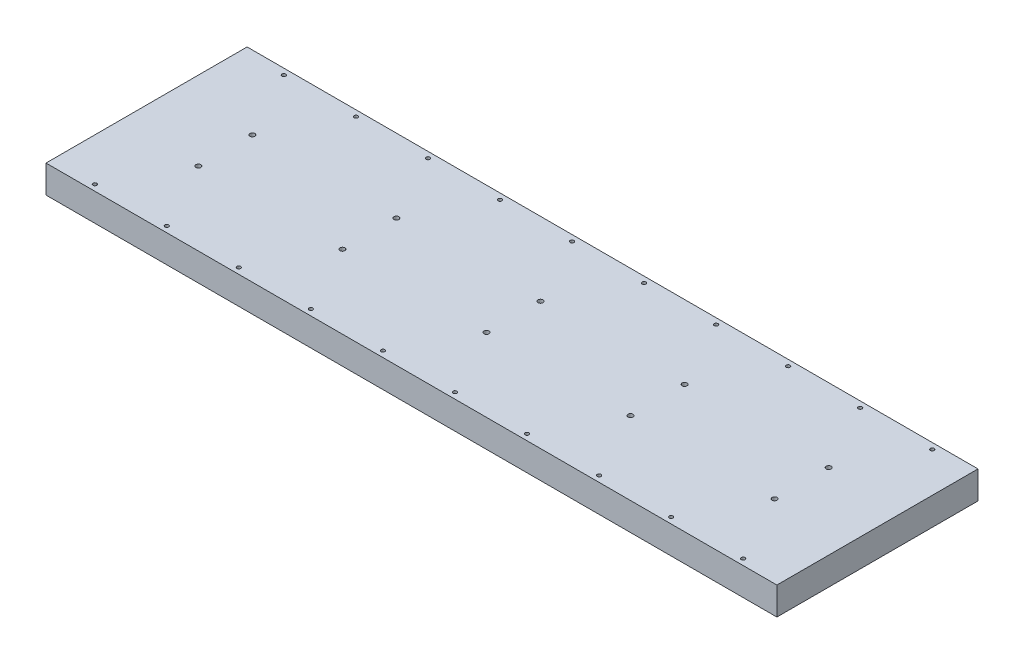
SolidWorks part; units mm, degrees
ref_plane "Front Plane" through (0, 0, 0) normal (0, 0, 1) x (1, 0, 0)
ref_plane "Top Plane" through (0, 0, 0) normal (0, 1, 0) x (1, 0, 0)
ref_plane "Right Plane" through (0, 0, 0) normal (1, 0, 0) x (0, 0, -1)
sketch "Sketch1" plane through (0, 0, 0) normal (0, 1, 0) x (1, 0, 0)
  line L1 (-243.5, 67) -> (243.5, 67)
  line L2 (-243.5, 67) -> (-243.5, -67)
  line L3 (-243.5, -67) -> (243.5, -67)
  line L4 (243.5, 67) -> (243.5, -67)
  line L5 (-243.5, 67) -> (243.5, -67) construction
  line L6 (-243.5, -67) -> (243.5, 67) construction
  point P0 (0, 0)
  dimension "D1" = 134
  dimension "D2" = 487
extrude "Boss-Extrude1" add sketch "Sketch1" along normal blind 18.5
hole_wizard "Tap Drill for M4x0.7 Tap1" positions "Sketch2" profile "Sketch3" hole size "M4x0.7" standard "ANSI Metric"
sketch "Sketch2" plane through (0, 18.5, 0) normal (0, 1, 0) x (1, 0, 0)
  line L0 (-191, -18) -> (-191, 18) construction
  line L3 (-243.5, 67) -> (-243.5, -67) construction
  point P0 (-191, 18)
  point P2 (-191, -18)
  point P10 (-191, 0)
  dimension "D1" = 36
  dimension "D2" = 52.5
sketch "Sketch3" plane through (-191, 18.5, -18) normal (1, 0, 0) x (0, 0, 1)
  line L0 (0, 0) -> (0, 18.3714)
  line L1 (0, 18.3714) -> (1.65, 17.38)
  line L2 (1.65, 17.38) -> (1.65, 0)
  line L5 (1.65, 0) -> (0, 0)
  line L10 (0, 18.3714) -> (-1.65, 17.38) construction
  line L11 (0, -6.35) -> (0, 107.95) construction
  dimension "Hole Dia." = 3.3
  dimension "Hole Depth" = 17.38
  dimension "Drill Angle" = 118
hole_wizard "Tap Drill for M3x0.5 Tap1" positions "Sketch4" profile "Sketch5" hole size "M3x0.5" standard "ANSI Metric"
sketch "Sketch4" plane through (0, 18.5, 0) normal (0, 1, 0) x (1, 0, 0)
  line L0 (-167, -63) -> (-167, 63) construction
  line L1 (-167, 63) -> (-215, 63) construction
  line L2 (-215, 63) -> (-215, -63) construction
  line L3 (-215, -63) -> (-167, -63) construction
  line L6 (-243.5, 67) -> (-243.5, -67) construction
  line L7 (-243.5, -67) -> (243.5, -67) construction
  point P2 (-215, 63)
  point P4 (-167, 63)
  point P6 (-167, -63)
  point P8 (-215, -63)
  point P26 (-215, 0)
  point P27 (-243.5, 0)
  point P28 (-191, 63)
  dimension "D1" = 48
  dimension "D2" = 126
sketch "Sketch5" plane through (-215, 18.5, -63) normal (1, 0, 0) x (0, 0, 1)
  line L0 (0, 0) -> (0, 18.1311)
  line L1 (0, 18.1311) -> (1.25, 17.38)
  line L2 (1.25, 17.38) -> (1.25, 0)
  line L5 (1.25, 0) -> (0, 0)
  line L10 (0, 18.1311) -> (-1.25, 17.38) construction
  line L11 (0, -6.35) -> (0, 107.95) construction
  dimension "Hole Dia." = 2.5
  dimension "Hole Depth" = 17.38
  dimension "Drill Angle" = 118
pattern_linear "LPattern1" count 5 spacing 96 along (1, 0, 0) of "Tap Drill for M3x0.5 Tap1", "Tap Drill for M4x0.7 Tap1"
